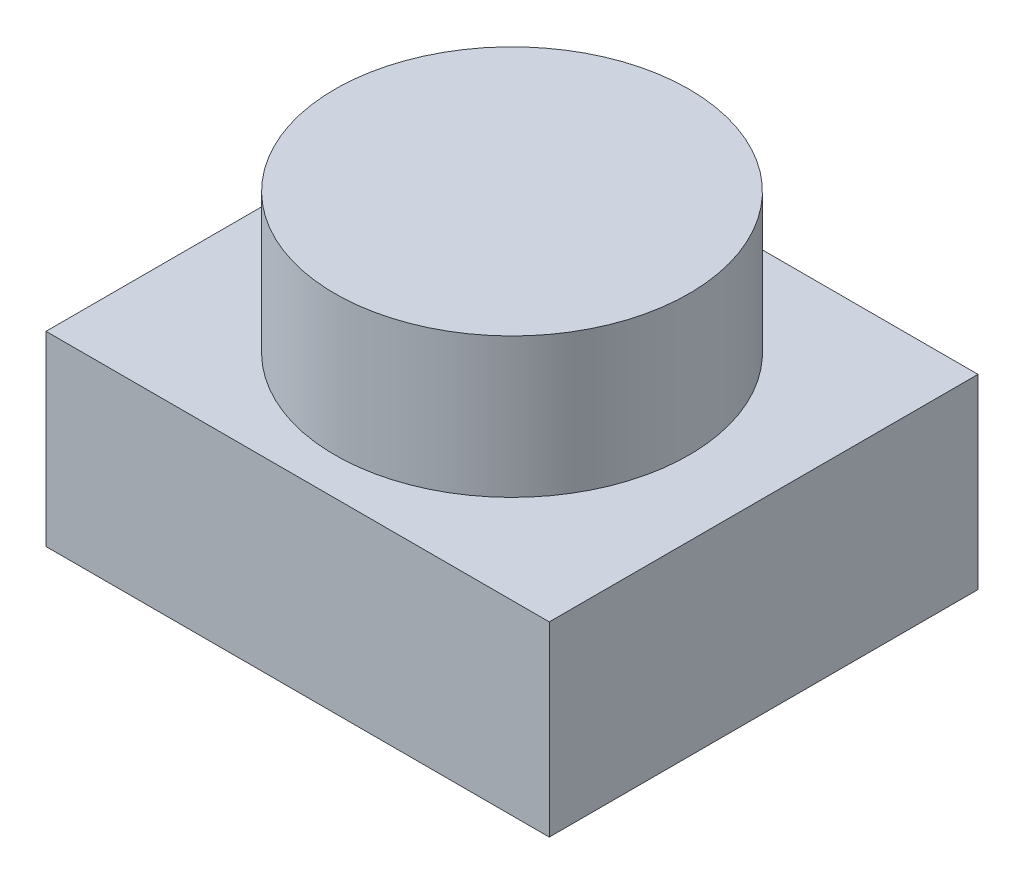
SolidWorks part; units mm, degrees
ref_plane "Front Plane" through (0, 0, 0) normal (0, 0, 1) x (1, 0, 0)
ref_plane "Top Plane" through (0, 0, 0) normal (0, 1, 0) x (1, 0, 0)
ref_plane "Right Plane" through (0, 0, 0) normal (1, 0, 0) x (0, 0, -1)
sketch "SK_Base" plane through (0, 0, 0) normal (0, 0, 1) x (1, 0, 0)
  line L0 (-27, 0) -> (27, 0)
  line L1 (27, 0) -> (27, 20)
  line L2 (27, 20) -> (-27, 20)
  line L3 (-27, 20) -> (-27, 0)
extrude "Base" add sketch "SK_Base" along normal mid plane 46
sketch "SK_Head" plane through (0, 0, 0) normal (0, 0, 1) x (1, 0, 0)
  line L0 (0, 20) -> (19, 20)
  line L1 (19, 20) -> (19, 35)
  line L2 (19, 35) -> (0, 35)
  line L3 (0, 35) -> (0, 20)
  line L4 (0, 15) -> (0, 40) construction
revolve "Head" add sketch "SK_Head" angle 360 about L4
